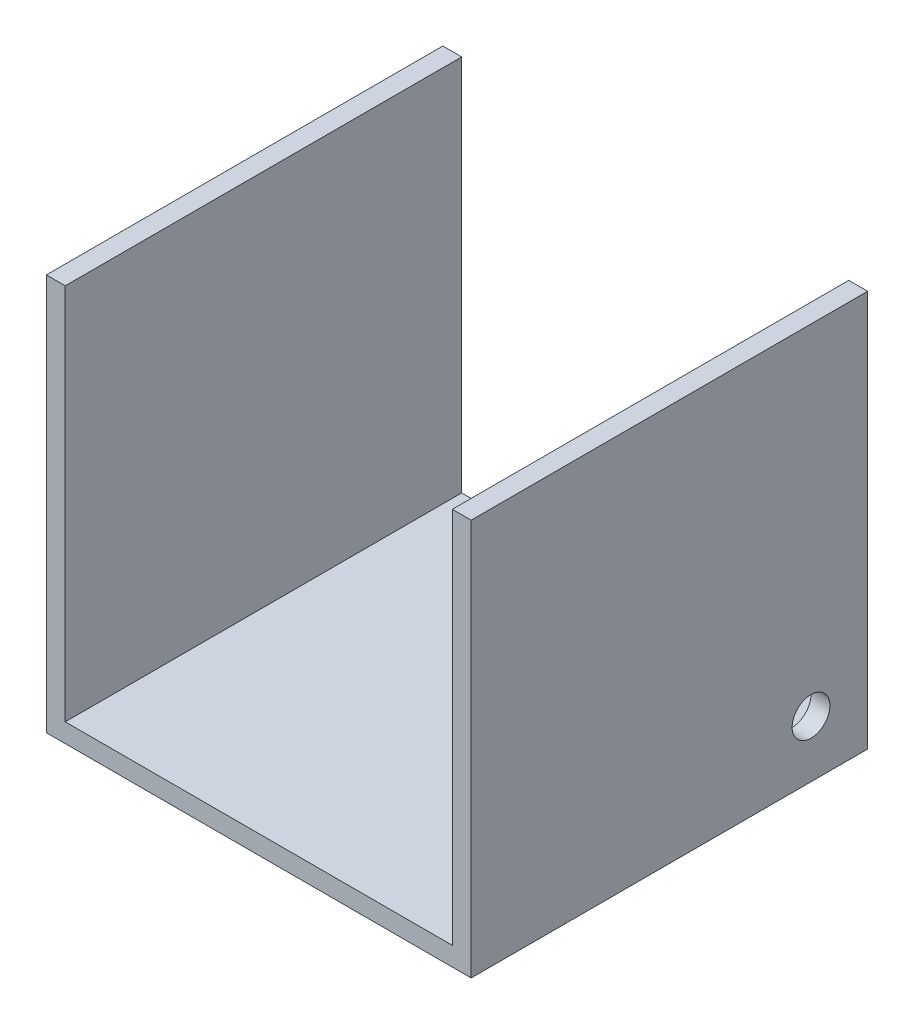
SolidWorks part; units mm, degrees
ref_plane "前视基准面" through (0, 0, 0) normal (0, 0, 1) x (1, 0, 0)
ref_plane "上视基准面" through (0, 0, 0) normal (0, 1, 0) x (1, 0, 0)
ref_plane "右视基准面" through (0, 0, 0) normal (1, 0, 0) x (0, 0, -1)
sketch "草图2" plane through (0, 0, 0) normal (0, 0, 1) x (1, 0, 0)
  line L0 (0, 0) -> (225, 0)
  line L1 (225, 0) -> (225, 210)
  line L2 (225, 210) -> (215, 210)
  line L3 (215, 210) -> (215, 10)
  line L4 (215, 10) -> (10, 10)
  line L5 (10, 10) -> (10, 210)
  line L6 (10, 210) -> (0, 210)
  line L7 (0, 210) -> (0, 0)
  dimension "D1" = 10
  dimension "D2" = 10
  dimension "D3" = 10
  dimension "D4" = 225
  dimension "D5" = 210
extrude "凸台-拉伸2" add sketch "草图2" against normal blind 210
sketch "草图3" plane through (225, 0, 0) normal (1, 0, 0) x (0, 0, -1)
  line L0 (210, 0) -> (0, 0) construction
  line L1 (210, 0) -> (210, 210) construction
  circle A0 centre (180, 30) radius 10
  dimension "D1" = 20
  dimension "D2" = 30
  dimension "D3" = 30
extrude "切除-拉伸1" cut sketch "草图3" against normal blind 10
hole_wizard "M2.5 六角头螺栓的柱形沉头孔1" positions "草图4" profile "草图5" counterbore size "M2.5" standard "GB" end condition through all
sketch "草图4" plane through (0, 10, 0) normal (0, 1, 0) x (1, 0, 0)
  line L0 (215, 210) -> (10, 210) construction
  line L1 (215, 210) -> (215, 0) construction
  point P0 (107, 180)
  point P2 (107, 131.4)
  point P4 (165, 131.4)
  point P6 (165, 180)
  dimension "D1" = 58
  dimension "D2" = 48.6
  dimension "D3" = 30
  dimension "D4" = 50
sketch "草图5" plane through (107, 10, -180) normal (1, 0, 0) x (0, 0, 1)
  line L0 (0, 0) -> (0, 10)
  line L1 (0, 10) -> (1.45, 10)
  line L3 (1.45, 10) -> (1.45, 0.5)
  line L4 (1.45, 0.5) -> (4, 0.5)
  line L5 (4, 0.5) -> (4, 0)
  line L7 (4, 0) -> (0, 0)
  line L11 (0, -6.35) -> (0, 107.95) construction
  dimension "通孔孔直径" = 2.9
  dimension "通孔孔深度" = 10
  dimension "柱形沉头孔直径" = 8
  dimension "柱形沉头孔深度" = 0.5
